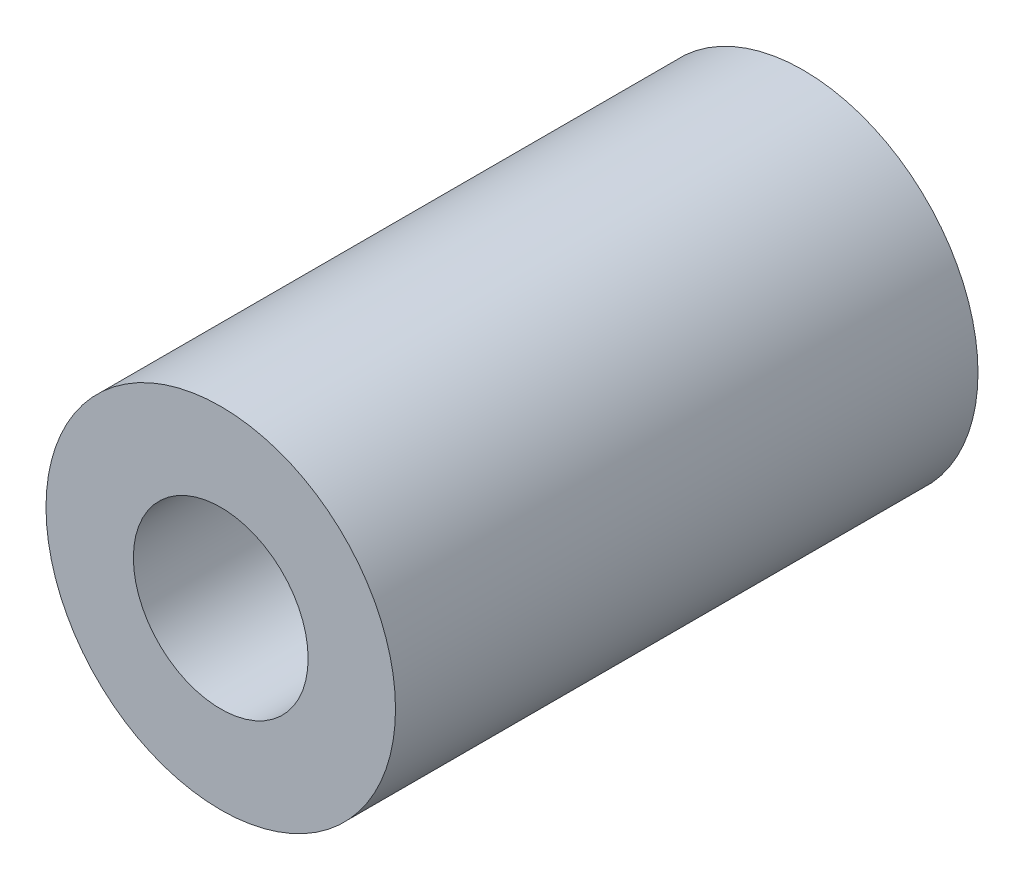
SolidWorks part; units mm, degrees
ref_plane "前视基准面" through (0, 0, 0) normal (0, 0, 1) x (1, 0, 0)
ref_plane "上视基准面" through (0, 0, 0) normal (0, 1, 0) x (1, 0, 0)
ref_plane "右视基准面" through (0, 0, 0) normal (1, 0, 0) x (0, 0, -1)
sketch "草图1" plane through (0, 0, 0) normal (0, 0, 1) x (1, 0, 0)
  circle A0 centre (0, 0) radius 3
  circle A1 centre (0, 0) radius 1.5
  dimension "D1" = 6
  dimension "D2" = 3
extrude "凸台-拉伸1" add sketch "草图1" along normal blind 10
